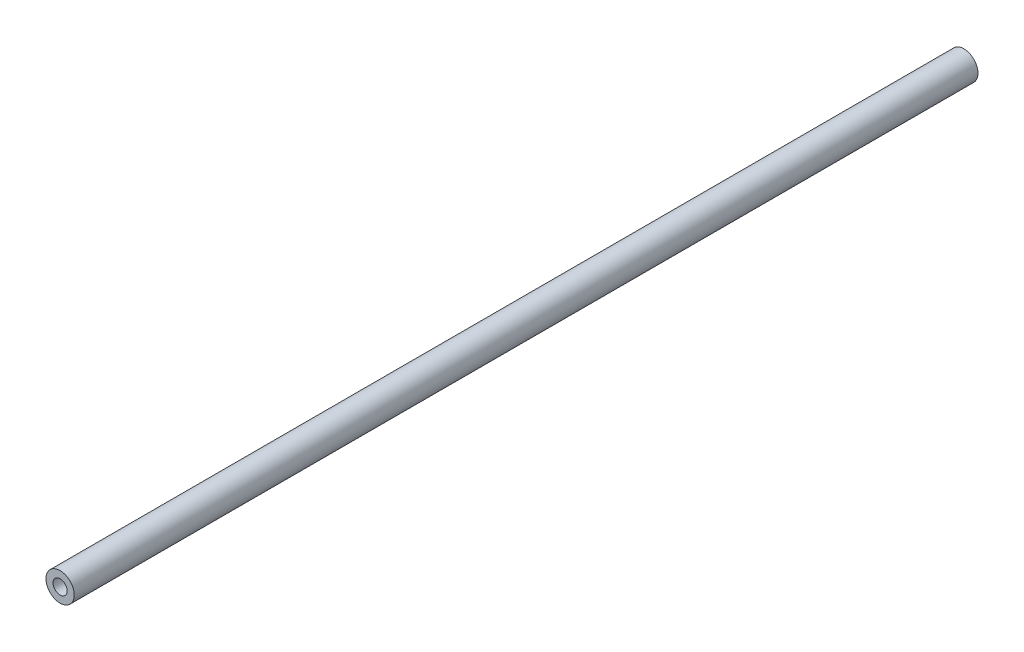
SolidWorks part; units mm, degrees
ref_plane "Front Plane" through (0, 0, 0) normal (0, 0, 1) x (1, 0, 0)
ref_plane "Top Plane" through (0, 0, 0) normal (0, 1, 0) x (1, 0, 0)
ref_plane "Right Plane" through (0, 0, 0) normal (1, 0, 0) x (0, 0, -1)
sketch "Sketch1" plane through (0, 0, 0) normal (0, 0, 1) x (1, 0, 0)
  circle A0 centre (0, 0) radius 6.35
  circle A1 centre (0, 0) radius 3.175
  dimension "D1" = 12.7
  dimension "D2" = 6.35
extrude "Boss-Extrude1" add sketch "Sketch1" along normal blind 406.4
